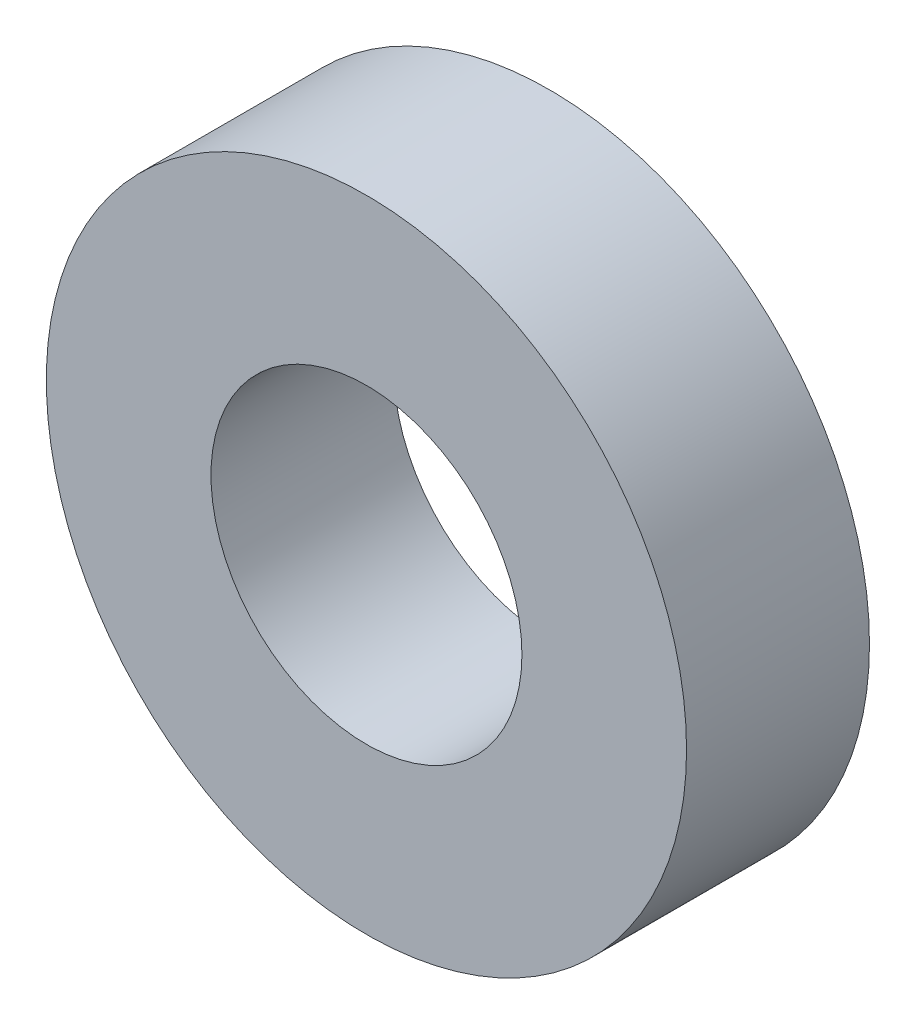
SolidWorks part; units mm, degrees
ref_plane "Front Plane" through (0, 0, 0) normal (0, 0, 1) x (1, 0, 0)
ref_plane "Top Plane" through (0, 0, 0) normal (0, 1, 0) x (1, 0, 0)
ref_plane "Right Plane" through (0, 0, 0) normal (1, 0, 0) x (0, 0, -1)
sketch "Sketch1" plane through (0, 0, 0) normal (0, 0, 1) x (1, 0, 0)
  circle A0 centre (0, 0) radius 8.5
  circle A1 centre (0, 0) radius 17.5
  dimension "D1" = 35
  dimension "D2" = 17
extrude "Boss-Extrude1" add sketch "Sketch1" along normal blind 10
